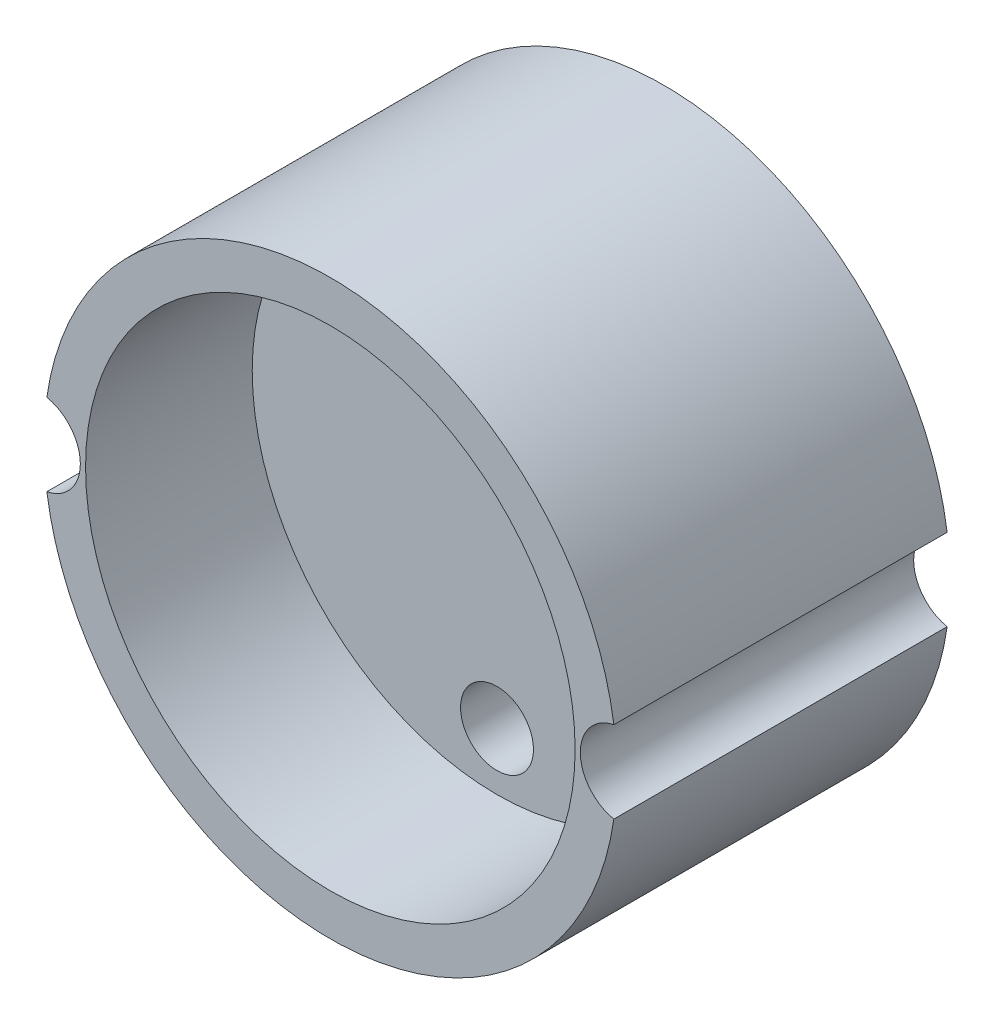
SolidWorks part; units mm, degrees
ref_plane "Front Plane" through (0, 0, 0) normal (1, 0, 0) x (0, 1, 0)
ref_plane "Top Plane" through (0, 0, 0) normal (0, 0, 1) x (0, 1, 0)
ref_plane "Right Plane" through (0, 0, 0) normal (0, 1, 0) x (-1, 0, 0)
sketch "Sketch1" plane through (0, 0, 0) normal (0, 0, 1) x (0, 1, 0)
  circle A0 centre (0, 0) radius 13.75
  point P3 (0, 0)
  dimension "D1" = 27.5
extrude "Boss-Extrude1" add sketch "Sketch1" along normal blind 16
sketch "Sketch2" plane through (0, 0, 16) normal (0, 0, 1) x (0, -1, 0)
  circle A0 centre (0, 0) radius 11.75
  dimension "D1" = 23.5
extrude "Cut-Extrude1" cut sketch "Sketch2" against normal blind 8
sketch "Sketch3" plane through (0, 0, 0) normal (0, 0, -1) x (1, 0, 0)
  line L0 (0, 9) -> (0, -9) construction
  circle A0 centre (0, 9) radius 1.75
  circle A1 centre (0, -9) radius 1.75
  dimension "D1" = 3.5
  dimension "D2" = 3.5
  dimension "D3" = 18
  dimension "D4" = 9
extrude "Cut-Extrude2" cut sketch "Sketch3" against normal through all
sketch "Sketch4" plane through (0, 0, 0) normal (0, 0, -1) x (1, 0, 0)
  line L0 (0, 0) -> (-14, 0) construction
  circle A0 centre (-14, 0) radius 2
  dimension "D1" = 4
  dimension "D2" = 14
extrude "Cut-Extrude4" cut sketch "Sketch4" against normal through all
mirror "Mirror1" about plane through (0, 0, 0) normal (1, 0, 0) of "Cut-Extrude4"
equation "\"D4@Sketch3\"=\"D3@Sketch3\"/2"
